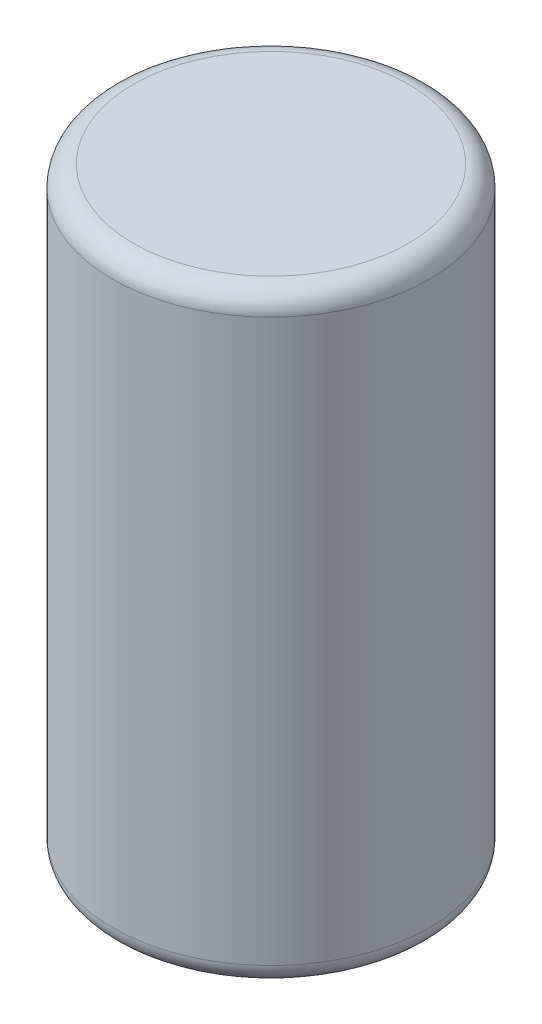
SolidWorks part; units mm, degrees
ref_plane "Front Plane" through (0, 0, 0) normal (0, 0, 1) x (1, 0, 0)
ref_plane "Top Plane" through (0, 0, 0) normal (0, 1, 0) x (1, 0, 0)
ref_plane "Right Plane" through (0, 0, 0) normal (1, 0, 0) x (0, 0, -1)
sketch "Sketch2" plane through (0, 0, 0) normal (0, 1, 0) x (1, 0, 0)
  circle A0 centre (0, 0) radius 76.2
  dimension "D1" = 152.4
extrude "Boss-Extrude1" add sketch "Sketch2" along normal blind 290
fillet "Fillet1" radius 10 2 edges at (0, 0, 76.2) (0, 290, 76.2)
